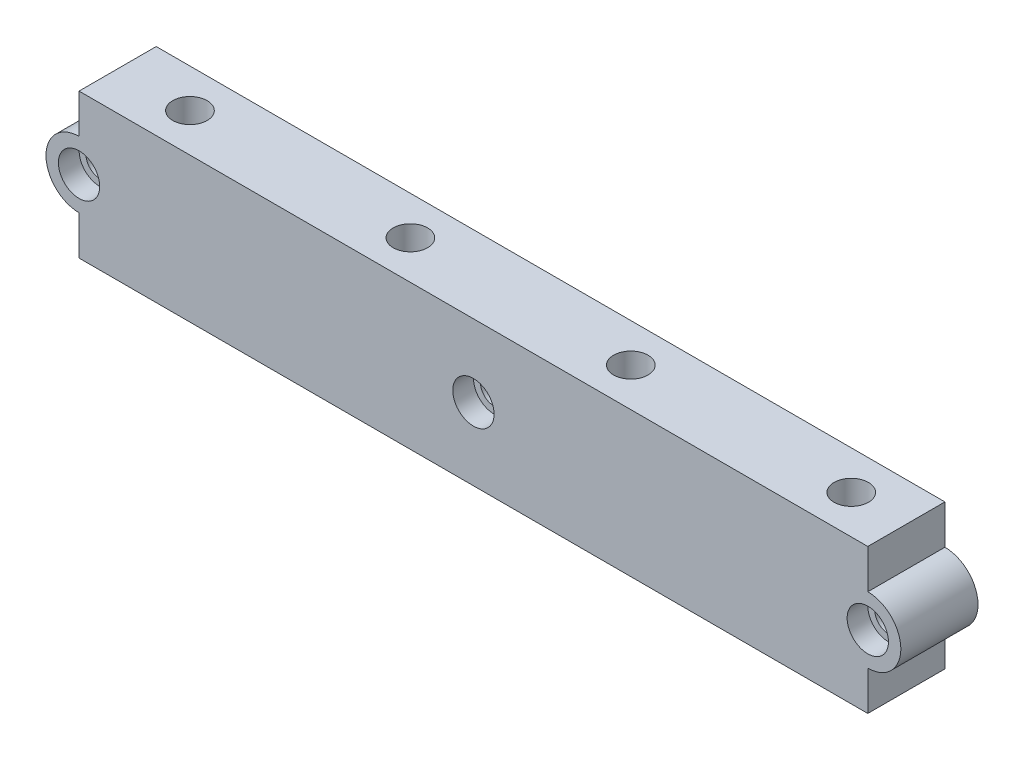
SolidWorks part; units mm, degrees
material "6061-T6 (SS)"
ref_plane "X-Y Datum" through (0, 0, 0) normal (0, 0, 1) x (1, 0, 0)
ref_plane "X-Z Datum" through (0, 0, 0) normal (0, 1, 0) x (1, 0, 0)
ref_plane "Y-Z Datum" through (0, 0, 0) normal (1, 0, 0) x (0, 0, -1)
sketch "Sketch1" plane through (0, 0, 0) normal (0, 0, 1) x (1, 0, 0)
  line L0 (0, 16.6688) -> (0, 7.62)
  line L1 (0, 16.6688) -> (-181.7687, 16.6687)
  line L5 (-8.7312, 0) -> (0, 0) construction
  line L6 (-181.7687, 16.6687) -> (-181.7687, 7.62)
  line L7 (-181.7687, 16.6687) -> (-181.7687, 0) construction
  line L8 (-8.7312, 0) -> (-16.6687, 0) construction
  line L9 (-8.7312, 0) -> (-8.7312, 16.6687) construction
  line L10 (-8.7312, 16.6687) -> (-16.6688, 16.6687) construction
  line L11 (-16.6687, 0) -> (-16.6688, 16.6687) construction
  line L12 (-67.4688, 0) -> (-59.5313, 0) construction
  line L13 (-67.4688, 0) -> (-67.4688, 16.6687) construction
  line L14 (-67.4688, 16.6687) -> (-59.5312, 16.6687) construction
  line L15 (-59.5313, 0) -> (-59.5312, 16.6687) construction
  line L16 (-181.7687, -7.62) -> (-181.7687, -16.6687)
  line L17 (-181.7687, -16.6687) -> (0, -16.6688)
  line L18 (0, -16.6688) -> (0, -7.62)
  line L20 (-110.3313, 16.6687) -> (-118.2688, 16.6687) construction
  line L21 (-110.3313, 16.6687) -> (-110.3312, 0) construction
  line L22 (-110.3312, 0) -> (-118.2688, 0) construction
  line L23 (-118.2688, 16.6687) -> (-118.2688, 0) construction
  line L24 (-161.1312, 16.6687) -> (-169.0687, 16.6687) construction
  line L25 (-161.1312, 16.6687) -> (-161.1312, 0) construction
  line L26 (-161.1312, 0) -> (-169.0687, 0) construction
  line L27 (-169.0687, 16.6687) -> (-169.0687, 0) construction
  circle A0 centre (0, 0) radius 3.175
  arc A2 (0, -7.62) -> (0, 7.62) centre (0, 0) ccw
  circle A4 centre (-181.7687, 0) radius 3.175
  arc A5 (-181.7687, 7.62) -> (-181.7687, -7.62) centre (-181.7687, 0) ccw
  circle A6 centre (-90.8844, 0) radius 3.175
  point P22 (-12.7, 0)
  point P23 (-63.5, 0)
  point P31 (-114.3, 0)
  point P32 (-165.1, 0)
  point P38 (-90.8844, -16.6687)
  dimension "D2" = 6.35
  dimension "D3" = 7.62
  dimension "D5" = 7.62
  dimension "D1" = 50.8
  dimension "D4" = 12.7
  dimension "D6" = 7.9375
  dimension "D7" = 7.9375
  dimension "D8" = 33.3375
  dimension "D11" = 50.8
  dimension "D12" = 50.8
  dimension "D13" = 12.7
extrude "Boss-Extrude1" add sketch "Sketch1" against normal blind 17.78
sketch "Sketch2" plane through (0, 16.6688, 0) normal (0, 1, 0) x (1, 0, 0)
  line L0 (-181.7687, 0) -> (0, 0) construction
  line L1 (0, 17.78) -> (0, 0) construction
  circle A0 centre (-12.7, 8.89) radius 3.9688
  circle A2 centre (-63.5, 8.89) radius 3.9688
  circle A3 centre (-114.3, 8.89) radius 3.9687
  circle A4 centre (-165.1, 8.89) radius 3.9688
  dimension "D2" = 7.9375
  dimension "D1" = 4
  dimension "D3" = 8.89
  dimension "D4" = 12.7
  dimension "D5" = 50.8
extrude "Cut-Extrude1" cut sketch "Sketch2" against normal up to surface (33.3375 mm away) up to face at (-90.8844, -16.6687, -8.89)
sketch "Sketch3" plane through (0, 0, 0) normal (0, 0, 1) x (1, 0, 0)
  circle A0 centre (0, 0) radius 4.7625
  circle A1 centre (-90.8844, 0) radius 4.7625
  circle A2 centre (-181.7687, 0) radius 4.7625
  dimension "D1" = 9.525
extrude "Cut-Extrude2" cut sketch "Sketch3" against normal blind 4.7752
